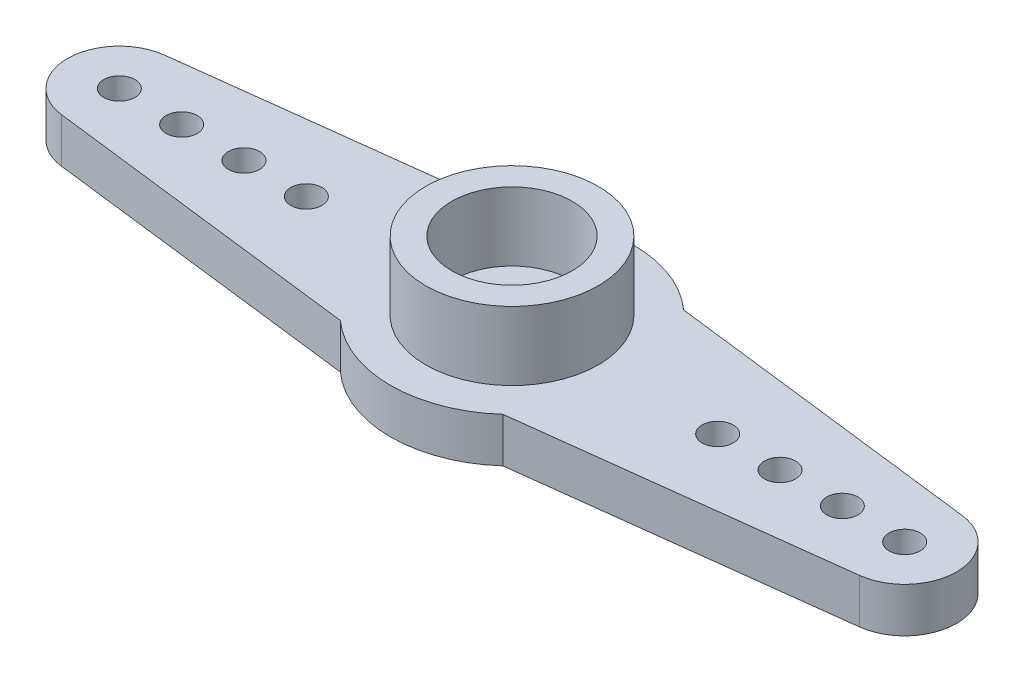
SolidWorks part; units mm, degrees
ref_plane "Front Plane" through (0, 0, 0) normal (0, 0, 1) x (1, 0, 0)
ref_plane "Top Plane" through (0, 0, 0) normal (0, 1, 0) x (1, 0, 0)
ref_plane "Right Plane" through (0, 0, 0) normal (1, 0, 0) x (0, 0, -1)
sketch "Sketch1" plane through (0, 0, 0) normal (0, 1, 0) x (1, 0, 0)
  line L0 (0, 18.3078) -> (0, -20.904) construction
  line L1 (-19.2032, 2.4815) -> (-3.9115, 4.35)
  line L2 (-19.2032, -2.4815) -> (-3.9115, -4.35)
  line L3 (-18.9, 0) -> (0, 0) construction
  line L4 (19.2032, -2.4815) -> (3.9115, -4.35)
  line L5 (19.2032, 2.4815) -> (3.9115, 4.35)
  circle A0 centre (0, 0) radius 5.85
  circle A1 centre (0, 0) radius 1.25
  arc A2 (-19.2032, -2.4815) -> (-19.2032, 2.4815) centre (-18.9, 0) cw
  circle A3 centre (-18.9, 0) radius 0.75
  circle A4 centre (-15.9, 0) radius 0.75
  circle A5 centre (-12.9, 0) radius 0.75
  circle A6 centre (-9.9, 0) radius 0.75
  circle A7 centre (9.9, 0) radius 0.75
  circle A8 centre (12.9, 0) radius 0.75
  circle A9 centre (15.9, 0) radius 0.75
  circle A10 centre (18.9, 0) radius 0.75
  arc A11 (19.2032, -2.4815) -> (19.2032, 2.4815) centre (18.9, 0) ccw
  dimension "D1" = 2.5
  dimension "D2" = 1.5
  dimension "D3" = 1.5
  dimension "D4" = 1.5
  dimension "D5" = 1.5
  dimension "D9" = 11.7
  dimension "D11" = 37.8
  dimension "D12" = 2.5
  dimension "D6" = 3
  dimension "D7" = 3
  dimension "D8" = 3
  dimension "D10" = 8.7
extrude "Boss-Extrude1" add sketch "Sketch1" along normal blind 2.15 contours A0 A1 | A2 L2 A0 L1 A6 A5 A4 A3 | L4 A11 L5 A0 A10 A8 A7 A9
sketch "Sketch2" plane through (0, 2.15, 0) normal (0, 1, 0) x (1, 0, 0)
  circle A0 centre (0, 0) radius 2.9
  circle A1 centre (0, 0) radius 4.15
  dimension "D1" = 8.3
  dimension "D2" = 5.8
extrude "Boss-Extrude2" add sketch "Sketch2" along normal blind 3.3
